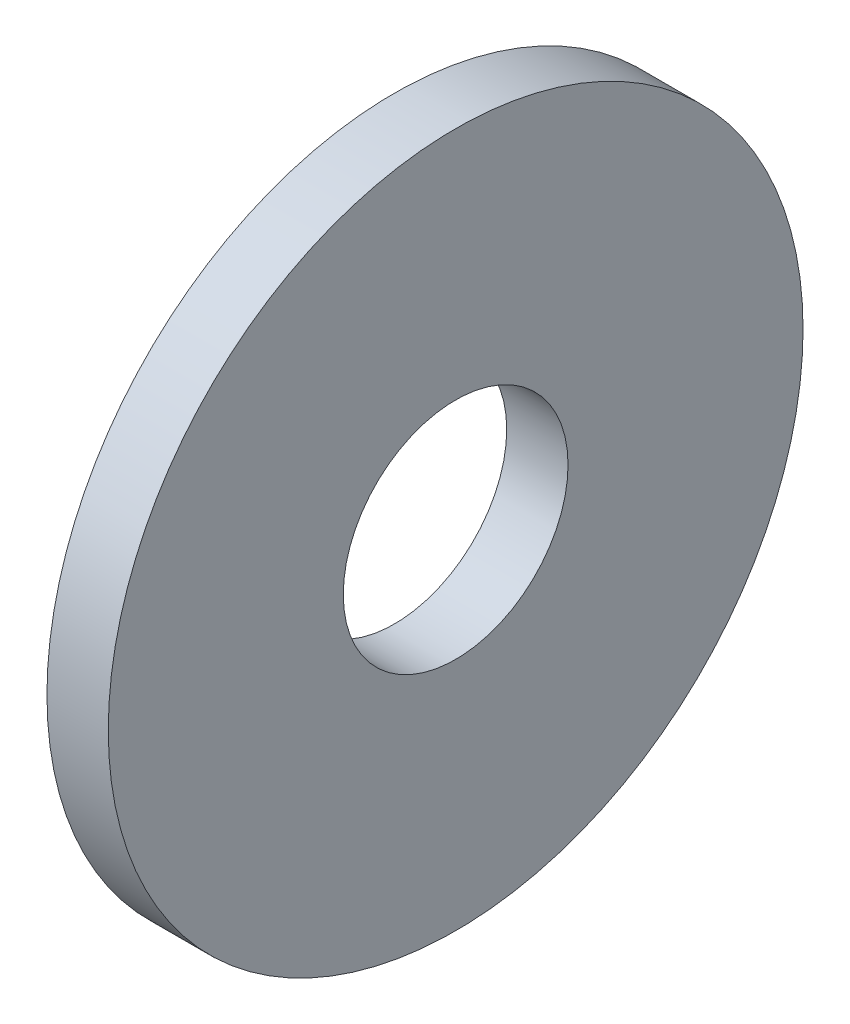
SolidWorks part; units mm, degrees
ref_plane "Plane1" through (0, 0, 0) normal (0, 0, 1) x (1, 0, 0)
ref_plane "Plane2" through (0, 0, 0) normal (0, 1, 0) x (1, 0, 0)
ref_plane "Plane3" through (0, 0, 0) normal (1, 0, 0) x (0, 0, -1)
sketch "Sketch1" plane through (0, 0, 0) normal (0, 0, 1) x (1, 0, 0)
  line L0 (-34.925, 0) -> (9.525, 0) construction
  line L1 (0, 5.5) -> (0, 17)
  line L2 (0, 17) -> (-3, 17)
  line L3 (-3, 17) -> (-3, 5.5)
  line L4 (-3, 5.5) -> (0, 5.5)
  dimension "Thickness" = 3
  dimension "Inside_dia" = 11
  dimension "Outside_dia" = 34
revolve "Base-Revolve" add sketch "Sketch1" angle 360 about L0
